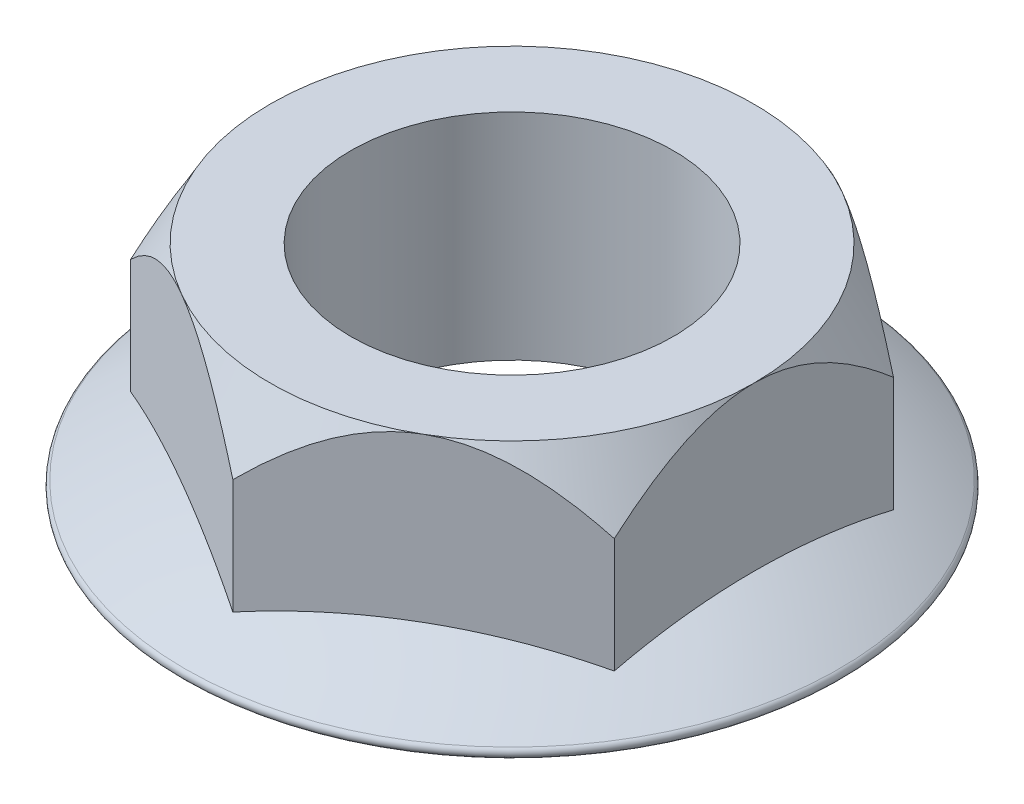
SolidWorks part; units mm, degrees
ref_plane "Front Plane" through (0, 0, 0) normal (0, 0, 1) x (1, 0, 0)
ref_plane "Top Plane" through (0, 0, 0) normal (0, 1, 0) x (1, 0, 0)
ref_plane "Right Plane" through (0, 0, 0) normal (1, 0, 0) x (0, 0, -1)
sketch "Sketch1" plane through (0, 0, 0) normal (0, 1, 0) x (1, 0, 0)
  line L1 (0, 25.9808) -> (-22.5, 12.9904)
  line L2 (-22.5, 12.9904) -> (-22.5, -12.9904)
  line L3 (-22.5, -12.9904) -> (0, -25.9808)
  line L4 (0, -25.9808) -> (22.5, -12.9904)
  line L5 (22.5, -12.9904) -> (22.5, 12.9904)
  line L6 (22.5, 12.9904) -> (0, 25.9808)
  circle A0 centre (0, 0) radius 22.5 construction
  circle A1 centre (0, 0) radius 15
  dimension "D2" = 30
  dimension "D1" = 45
extrude "Boss-Extrude1" add sketch "Sketch1" along normal blind 20
sketch "Sketch3" plane through (0, 0, 0) normal (0, 0, 1) x (1, 0, 0)
  line L0 (0, 0) -> (0, -50000) construction
  line L1 (0, 0) -> (22.5, 0) construction
  line L2 (0, 9.2142) -> (0, 0)
  line L3 (0, 0) -> (30.1665, 0)
  arc A0 (0, 9.2142) -> (30.42, 0.931) centre (0, -50.7858) cw
  arc A1 (30.42, 0.931) -> (30.1665, 0) centre (30.1665, 0.5) cw
  point P12 (31.95, 0)
  dimension "D2" = 60
  dimension "D3" = 0.5
  dimension "D1" = 31.95
revolve "Revolve1" add sketch "Sketch3" angle 360 about L0
sketch "Sketch2" plane through (0, 20, 0) normal (0, 1, 0) x (1, 0, 0)
  line L0 (0, 25.9808) -> (-22.5, 12.9904) construction
  circle A0 centre (0, 0) radius 22.5
extrude "Cut-Extrude1" cut sketch "Sketch2" against normal blind 20 draft 30 flip side to cut
sketch "Sketch4" plane through (0, 20, 0) normal (0, 1, 0) x (1, 0, 0)
  circle A0 centre (0, 0) radius 15 construction
  circle A1 centre (0, 0) radius 15
extrude "Cut-Extrude2" cut sketch "Sketch4" against normal up to next
